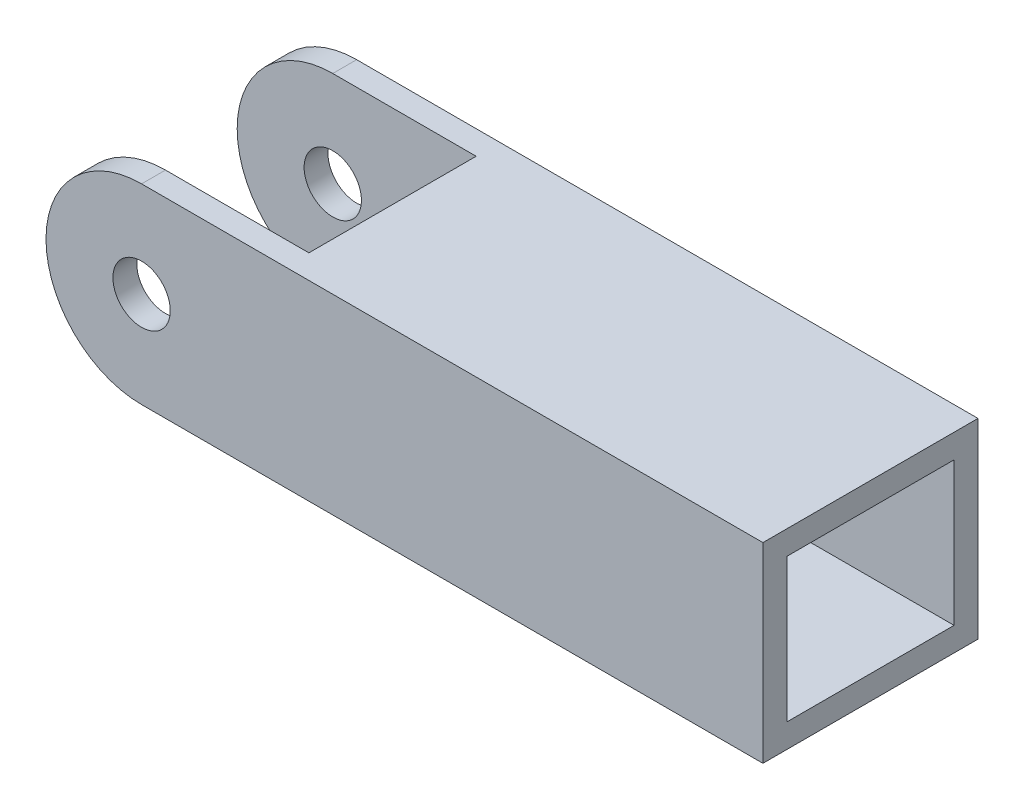
SolidWorks part; units mm, degrees
ref_plane "Płaszczyzna przednia" through (0, 0, 0) normal (0, 0, 1) x (1, 0, 0)
ref_plane "Płaszczyzna górna" through (0, 0, 0) normal (0, 1, 0) x (1, 0, 0)
ref_plane "Płaszczyzna prawa" through (0, 0, 0) normal (1, 0, 0) x (0, 0, -1)
sketch "Szkic1" plane through (0, 0, 0) normal (0, 0, 1) x (1, 0, 0)
  line L1 (-65, -20) -> (65, -20)
  line L3 (-65, 20) -> (65, 20)
  line L4 (65, -20) -> (65, 20)
  line L5 (-65, -20) -> (65, 20) construction
  line L6 (-65, 20) -> (65, -20) construction
  arc A0 (-65, -20) -> (-65, 20) centre (-65, 0) cw
  point P0 (0, 0)
  dimension "D1" = 40
  dimension "D2" = 130
extrude "Dodanie-wyciągnięcie1" add sketch "Szkic1" along normal blind 5 contours L3 L4 L1 A0
ref_plane "Płaszczyzna1" through (0, 0, 22.5) normal (0, 0, 1) x (1, 0, 0)
mirror "Lustro2" about plane through (0, 0, 22.5) normal (0, 0, 1) of bodies 101
ref_plane "Płaszczyzna2" through (0, 20, 0) normal (0, 1, 0) x (1, 0, 0)
sketch "Szkic2" plane through (0, 20, 0) normal (0, 1, 0) x (1, 0, 0)
  line L0 (-65, -5) -> (65, -5) construction
  line L1 (65, -40) -> (-35, -40)
  line L2 (65, -40) -> (65, -5)
  line L3 (65, -5) -> (-35, -5)
  line L4 (-35, -40) -> (-35, -5)
  line L5 (65, -5) -> (65, 0) construction
  dimension "D1" = 100
  dimension "D2" = 35
extrude "Dodanie-wyciągnięcie2" add sketch "Szkic2" against normal blind 5
sketch "Szkic3" plane through (0, 0, 0) normal (0, 0, -1) x (-1, 0, 0)
  circle A0 centre (65, 0) radius 6
  arc A1 (65, -20) -> (65, 20) centre (65, 0) ccw construction
  dimension "D1" = 12
extrude "Wytnij-wyciągnięcie1" cut sketch "Szkic3" against normal through all
sketch "Szkic4" plane through (0, -20, 0) normal (0, -1, 0) x (1, 0, 0)
  line L1 (65, 40) -> (-35, 40)
  line L2 (65, 40) -> (65, 0)
  line L3 (65, 0) -> (-35, 0)
  line L4 (-35, 40) -> (-35, 0)
  dimension "D1" = 40
  dimension "D2" = 100
extrude "Dodanie-wyciągnięcie3" add sketch "Szkic4" against normal blind 5 contours L3 L4 L1 L2
